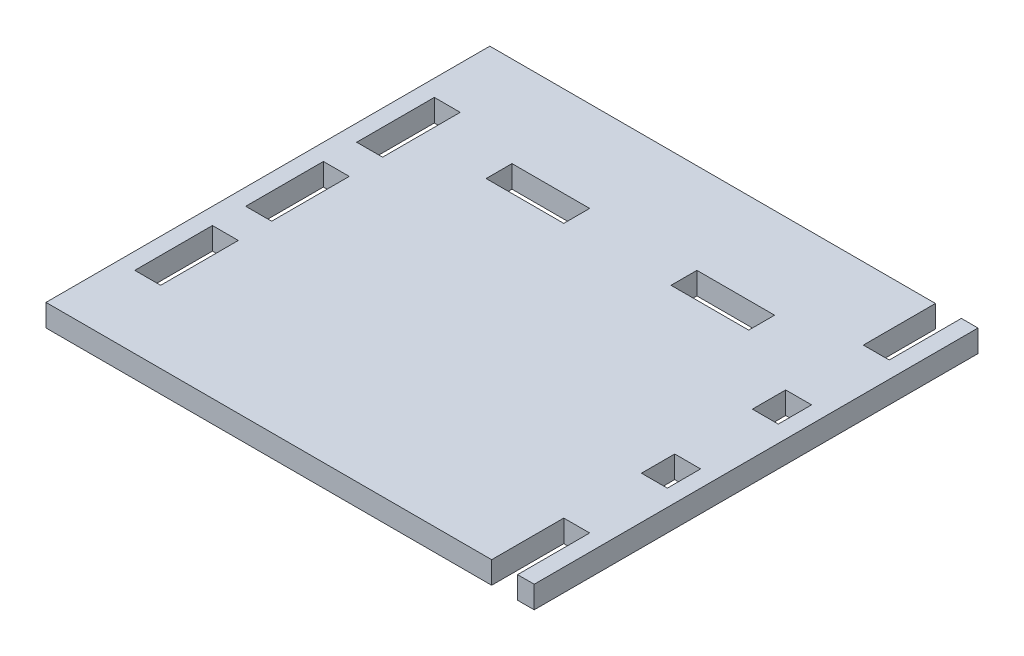
SolidWorks part; units mm, degrees
ref_plane "Спереди" through (0, 0, 0) normal (0, 0, 1) x (1, 0, 0)
ref_plane "Сверху" through (0, 0, 0) normal (0, 1, 0) x (1, 0, 0)
ref_plane "Справа" through (0, 0, 0) normal (1, 0, 0) x (0, 0, -1)
sketch "Эскиз1" plane through (0, 0, 0) normal (0, 1, 0) x (1, 0, 0)
  line L0 (-30.75, 10.7991) -> (-27.25, 10.7991)
  line L1 (33, -24.4509) -> (-33, -24.4509) construction
  line L2 (33, -24.4509) -> (33, 35.5491) construction
  line L3 (33, 35.5491) -> (-33, 35.5491) construction
  line L4 (-33, -24.4509) -> (-33, 35.5491) construction
  line L5 (-30.75, 25.7991) -> (-27.25, 25.7991)
  line L6 (-30.75, 25.7991) -> (-30.75, 15.2991)
  line L7 (-30.75, 15.2991) -> (-27.25, 15.2991)
  line L8 (-27.25, 25.7991) -> (-27.25, 15.2991)
  line L9 (-30.75, 10.7991) -> (-30.75, 0.2991)
  line L10 (-30.75, 0.2991) -> (-27.25, 0.2991)
  line L11 (-27.25, 10.7991) -> (-27.25, 0.2991)
  line L12 (-30.75, -4.2009) -> (-27.25, -4.2009)
  line L13 (-30.75, -4.2009) -> (-30.75, -14.7009)
  line L14 (-30.75, -14.7009) -> (-27.25, -14.7009)
  line L15 (-27.25, -4.2009) -> (-27.25, -14.7009)
  line L16 (0, -24.4509) -> (0, 0) construction
  line L17 (7.25, 23.2991) -> (7.25, 19.7991)
  line L18 (17.75, 19.7991) -> (7.25, 19.7991)
  line L19 (17.75, 23.2991) -> (17.75, 19.7991)
  line L20 (17.75, 23.2991) -> (7.25, 23.2991)
  line L21 (0, 0) -> (14.682, 0) construction
  line L22 (30.75, -14.7009) -> (27.25, -14.7009)
  line L23 (27.25, 10.7991) -> (30.75, 10.7991)
  line L24 (30.75, -4.2009) -> (27.25, -4.2009)
  line L25 (30.75, 10.7991) -> (30.75, 15.2991)
  line L26 (30.75, 0.2991) -> (27.25, 0.2991)
  line L27 (30.75, 15.2991) -> (27.25, 15.2991)
  line L28 (27.25, 15.2991) -> (27.25, 10.7991)
  line L29 (27.25, 25.7991) -> (27.25, 35.5491)
  line L30 (-17.75, 23.2991) -> (-7.25, 23.2991)
  line L31 (-17.75, 23.2991) -> (-17.75, 19.7991)
  line L32 (-17.75, 19.7991) -> (-7.25, 19.7991)
  line L33 (-7.25, 23.2991) -> (-7.25, 19.7991)
  line L34 (27.25, 35.5491) -> (30.75, 35.5491)
  line L35 (30.75, 35.5491) -> (30.75, 25.7991)
  line L36 (30.75, 25.7991) -> (27.25, 25.7991)
  line L37 (30.75, -4.2009) -> (30.75, 0.2991)
  line L46 (27.25, 0.2991) -> (27.25, -4.2009)
  line L47 (30.75, -14.7009) -> (30.75, -24.4509)
  line L48 (30.75, -24.4509) -> (27.25, -24.4509)
  line L49 (27.25, -24.4509) -> (27.25, -14.7009)
  dimension "D1" = 60
  dimension "D3" = 3.5
  dimension "D4" = 10.5
  dimension "D5" = 9.75
  dimension "D7" = 4.5
  dimension "D8" = 2.25
  dimension "D10" = 3.5
  dimension "D11" = 10.5
  dimension "D12" = 15.25
  dimension "D13" = 12.25
  dimension "D14" = 66
  dimension "D6" = 3
sketch "Эскиз3" plane through (0, 0, 0) normal (0, 1, 0) x (1, 0, 0)
  line L0 (-33, 35.5491) -> (-33, -24.4509)
  line L1 (-33, -24.4509) -> (33, -24.4509)
  line L2 (33, -24.4509) -> (33, 35.5491)
  line L3 (33, 35.5491) -> (-33, 35.5491)
extrude "Бобышка-Вытянуть1" add sketch "Эскиз3" along normal blind 3
extrude "Вырез-Вытянуть1" cut sketch "Эскиз1" along normal through all
